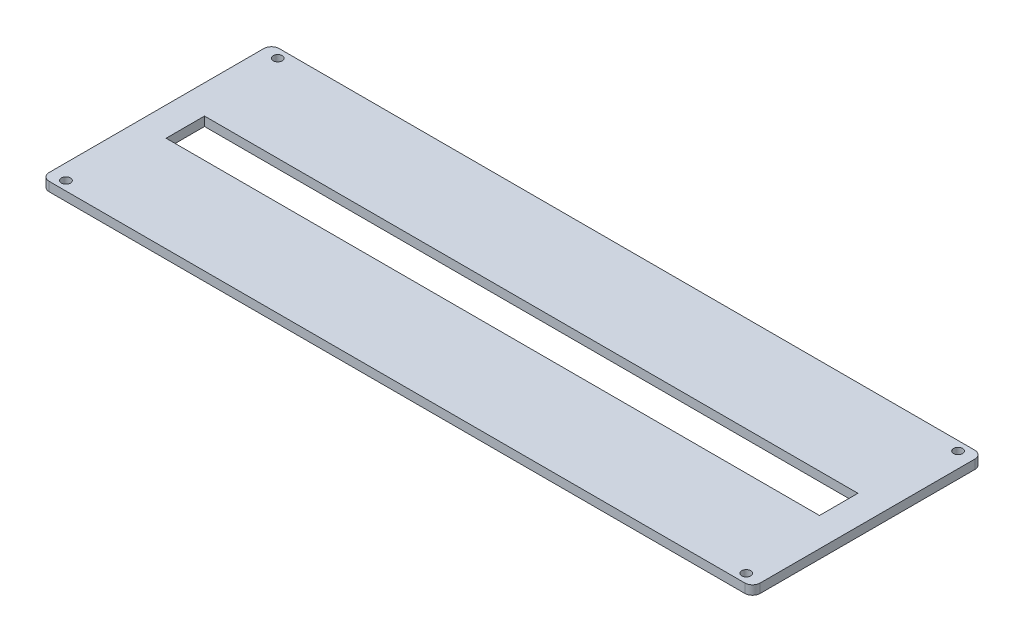
SolidWorks part; units mm, degrees
ref_plane "Front Plane" through (0, 0, 0) normal (0, 0, 1) x (1, 0, 0)
ref_plane "Top Plane" through (0, 0, 0) normal (0, 1, 0) x (1, 0, 0)
ref_plane "Right Plane" through (0, 0, 0) normal (1, 0, 0) x (0, 0, -1)
sketch "Sketch3" plane through (0, 0, 0) normal (0, 1, 0) x (1, 0, 0)
  line L0 (0, -38) -> (-234.95, -38) construction
  line L1 (0, -76) -> (-234.95, -76)
  line L2 (0, -76) -> (0, 0)
  line L3 (0, 0) -> (-234.95, 0)
  line L4 (-234.95, -76) -> (-234.95, 0)
  line L6 (-117.475, 0) -> (-117.475, -76) construction
  circle A0 centre (-5.08, -3) radius 1.5
  circle A4 centre (-5.08, -73) radius 1.5
  circle A5 centre (-229.87, -73) radius 1.5
  circle A6 centre (-229.87, -3) radius 1.5
  point P0 (0, 0)
  dimension "D1" = 76
  dimension "D6" = 3
  dimension "D2" = 0
  dimension "D3" = 234.95
  dimension "D4" = 3
  dimension "D5" = 5.08
extrude "Boss-Extrude4" add sketch "Sketch3" along normal blind 3
sketch "Sketch4" plane through (0, 3, 0) normal (0, 1, 0) x (1, 0, 0)
  line L0 (-234.95, -38) -> (0, -38) construction
  line L2 (-234.95, -76) -> (-234.95, 0) construction
  line L3 (0, -76) -> (0, 0) construction
  line L5 (-9.525, -31.65) -> (-225.425, -31.65)
  line L6 (-9.525, -31.65) -> (-9.525, -44.35)
  line L7 (-9.525, -44.35) -> (-225.425, -44.35)
  line L8 (-225.425, -31.65) -> (-225.425, -44.35)
  line L9 (-9.525, -31.65) -> (-225.425, -44.35) construction
  line L10 (-9.525, -44.35) -> (-225.425, -31.65) construction
  point P6 (-117.475, -38)
  dimension "D1" = 215.9
  dimension "D2" = 12.7
extrude "Cut-Extrude1" cut sketch "Sketch4" against normal blind 3.81 contours L5 L8 L7 L6
fillet "Fillet11" radius 2.54 4 edges at (0, 1.5, 76) (0, 1.5, 0) (-234.95, 1.5, 0) (-234.95, 1.5, 76)
